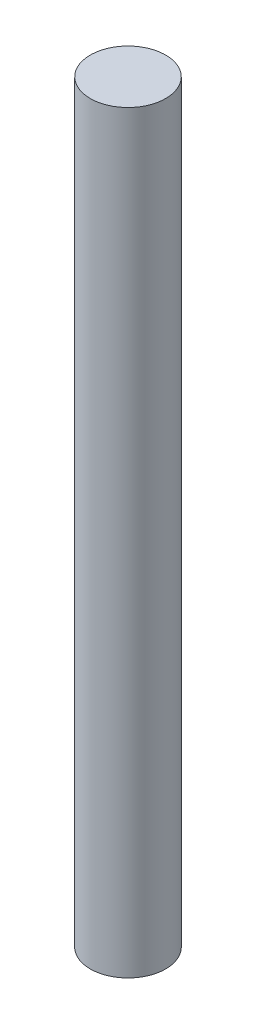
SolidWorks part; units mm, degrees
material "3.0255 (EN-AW 1350A)"
ref_plane "Alzado" through (0, 0, 0) normal (0, 0, 1) x (1, 0, 0)
ref_plane "Planta" through (0, 0, 0) normal (0, 1, 0) x (1, 0, 0)
ref_plane "Vista lateral" through (0, 0, 0) normal (1, 0, 0) x (0, 0, -1)
sketch "Croquis1" plane through (0, 0, 0) normal (0, 1, 0) x (1, 0, 0)
  circle A0 centre (0, 0) radius 0.35
  dimension "D1" = 0.7
extrude "Saliente-Extruir1" add sketch "Croquis1" along normal blind 7
